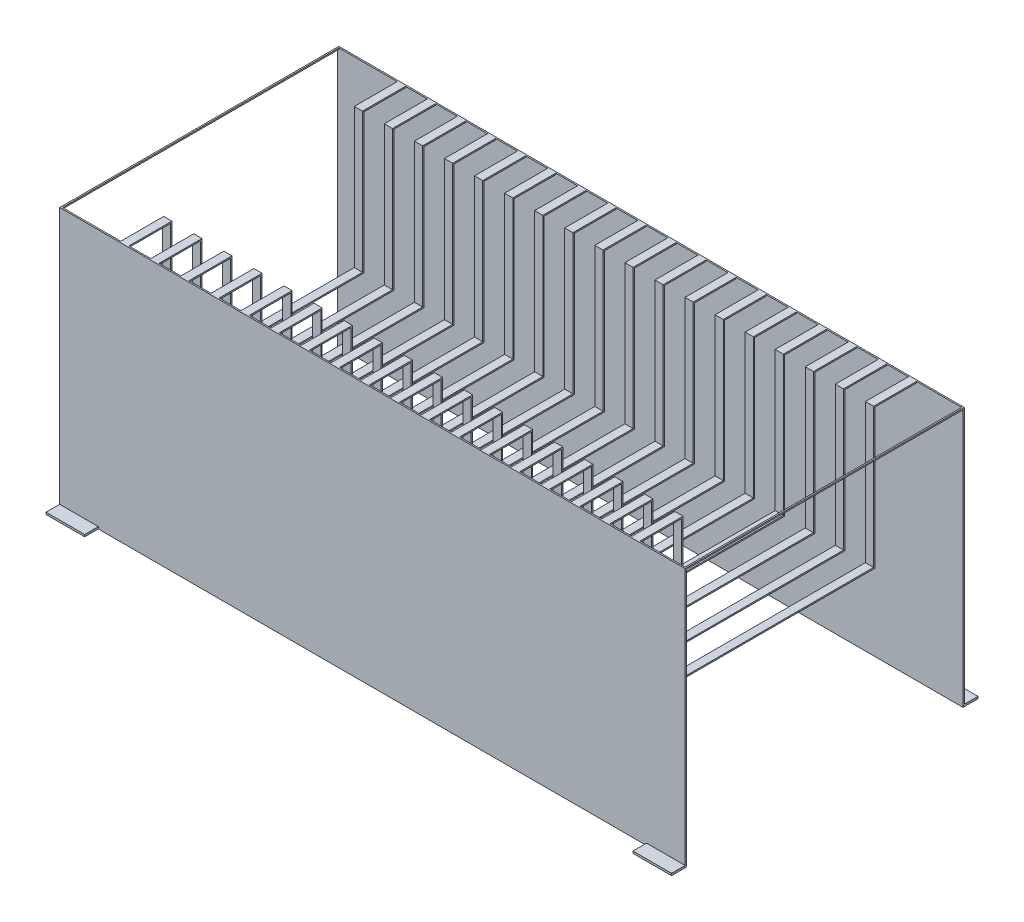
SolidWorks part; units mm, degrees
ref_plane "Alzado" through (0, 0, 0) normal (0, 0, 1) x (1, 0, 0)
ref_plane "Planta" through (0, 0, 0) normal (0, 1, 0) x (1, 0, 0)
ref_plane "Vista lateral" through (0, 0, 0) normal (1, 0, 0) x (0, 0, -1)
sketch "Croquis1" plane through (0, 0, 0) normal (0, 0, 1) x (1, 0, 0)
  line L0 (0, 0) -> (0, 1200)
  line L1 (0, 0) -> (2900, 0)
  line L2 (2900, 0) -> (2900, 1200)
  line L3 (2900, 1200) -> (0, 1200) construction
  line L4 (2906.35, -6.35) -> (2906.35, 1200)
  line L5 (-6.35, -6.35) -> (2906.35, -6.35)
  line L6 (-6.35, -6.35) -> (-6.35, 1200)
  line L7 (0, 1200) -> (-6.35, 1200)
  line L8 (2900, 1200) -> (2906.35, 1200)
  dimension "D1" = 1200
  dimension "D2" = 2900
  dimension "D3" = 6.35
extrude "Saliente-Extruir1" add sketch "Croquis1" along normal blind 1300
sketch "Croquis2" plane through (0, 0, 1300) normal (0, 0, 1) x (1, 0, 0)
  line L1 (-6.35, 1200) -> (2906.35, 1200)
  line L2 (-6.35, 1200) -> (-6.35, -6.35)
  line L3 (-6.35, -6.35) -> (2906.35, -6.35)
  line L4 (2906.35, 1200) -> (2906.35, -6.35)
extrude "Saliente-Extruir2" add sketch "Croquis2" against normal blind 6.35
sketch "Croquis3" plane through (0, 0, 0) normal (0, 0, -1) x (-1, 0, 0)
  line L1 (-2906.35, 1200) -> (6.35, 1200)
  line L2 (-2906.35, 1200) -> (-2906.35, -6.35)
  line L3 (-2906.35, -6.35) -> (6.35, -6.35)
  line L4 (6.35, 1200) -> (6.35, -6.35)
extrude "Saliente-Extruir3" add sketch "Croquis3" against normal blind 6.35
sketch "Croquis4" plane through (0, 1200, 0) normal (0, 1, 0) x (1, 0, 0)
  line L0 (2900, -1293.65) -> (0, -1293.65) construction
  line L1 (2690, -1293.65) -> (2651.9, -1293.65)
  line L2 (2690, -1293.65) -> (2690, -1093.65)
  line L3 (2690, -1093.65) -> (2651.9, -1093.65)
  line L4 (2651.9, -1293.65) -> (2651.9, -1093.65)
  line L5 (2900, -1293.65) -> (2900, -6.35) construction
  line L6 (2900, -650) -> (2322.7282, -650) construction
  line L7 (2900, -1293.65) -> (2900, -6.35) construction
  line L8 (2651.9, -6.35) -> (2651.9, -206.35)
  line L9 (2690, -206.35) -> (2651.9, -206.35)
  line L10 (2690, -6.35) -> (2690, -206.35)
  line L11 (2690, -6.35) -> (2651.9, -6.35)
  dimension "D1" = 210
  dimension "D2" = 38.1
  dimension "D3" = 200
extrude "Saliente-Extruir4" add sketch "Croquis4" against normal blind 6.35
pattern_linear "MatrizL1" count 18 spacing 140 along (-1, 0, 0) of "Saliente-Extruir4"
sketch "Croquis5" plane through (-6.35, 0, 0) normal (-1, 0, 0) x (0, 0, 1)
  line L1 (1293.65, 1193.65) -> (6.35, 1193.65)
  line L2 (1293.65, 1193.65) -> (1293.65, -13.1397)
  line L3 (1293.65, -13.1397) -> (6.35, -13.1397)
  line L4 (6.35, 1193.65) -> (6.35, -13.1397)
extrude "Cortar-Extruir1" cut sketch "Croquis5" against normal up to surface (2912.7 mm away) up to face at (2906.35, 596.825, 650)
sketch "Croquis6" plane through (0, 1193.65, 0) normal (0, -1, 0) x (1, 0, 0)
  line L0 (310, 206.35) -> (310, 6.35) construction
  line L1 (271.9, 206.35) -> (310, 206.35)
  line L2 (271.9, 206.35) -> (271.9, 200)
  line L3 (271.9, 200) -> (310, 200)
  line L4 (310, 206.35) -> (310, 200)
  dimension "D1" = 6.35
extrude "Saliente-Extruir5" add sketch "Croquis6" along normal blind 650
pattern_linear "MatrizL2" count 18 spacing 140 along (1, 0, 0) of "Saliente-Extruir5"
sketch "Croquis7" plane through (0, 1193.65, 0) normal (0, -1, 0) x (1, 0, 0)
  line L0 (2651.9, 1093.65) -> (2651.9, 1293.65) construction
  line L1 (2690, 1093.65) -> (2651.9, 1093.65)
  line L2 (2690, 1093.65) -> (2690, 1100)
  line L3 (2690, 1100) -> (2651.9, 1100)
  line L4 (2651.9, 1093.65) -> (2651.9, 1100)
  dimension "D1" = 6.35
extrude "Saliente-Extruir6" add sketch "Croquis7" along normal blind 650
pattern_linear "MatrizL3" count 18 spacing 140 along (-1, 0, 0) of "Saliente-Extruir6"
sketch "Croquis8" plane through (0, 0, 1093.65) normal (0, 0, -1) x (-1, 0, 0)
  line L0 (-2651.9, 543.65) -> (-2651.9, 1200) construction
  line L1 (-2690, 543.65) -> (-2651.9, 543.65)
  line L2 (-2690, 543.65) -> (-2690, 550)
  line L3 (-2690, 550) -> (-2651.9, 550)
  line L4 (-2651.9, 543.65) -> (-2651.9, 550)
  dimension "D1" = 6.35
extrude "Saliente-Extruir7" add sketch "Croquis8" along normal up to surface (887.3 mm away) up to face at (2670.95, 871.825, 206.35)
pattern_linear "MatrizL4" count 18 spacing 140 along (-1, 0, 0) of "Saliente-Extruir7"
sketch "Croquis9" plane through (0, -6.35, 0) normal (0, -1, 0) x (1, 0, 0)
  line L0 (2906.35, 650) -> (-120.3286, 650) construction
  line L1 (2906.35, 1300) -> (2726.35, 1300)
  line L2 (2906.35, 1300) -> (2906.35, 1363.5)
  line L3 (2906.35, 1363.5) -> (2726.35, 1363.5)
  line L4 (2726.35, 1300) -> (2726.35, 1363.5)
  line L5 (2906.35, 6.35) -> (2906.35, 1293.65) construction
  line L6 (2726.35, 0) -> (2726.35, -63.5)
  line L7 (2906.35, -63.5) -> (2726.35, -63.5)
  line L8 (2906.35, 0) -> (2906.35, -63.5)
  line L9 (2906.35, 0) -> (2726.35, 0)
  line L10 (1450, 1300) -> (1450, 748.066) construction
  line L11 (-6.35, 1300) -> (2906.35, 1300) construction
  line L12 (-6.35, 0) -> (173.65, 0)
  line L13 (-6.35, 0) -> (-6.35, -63.5)
  line L14 (-6.35, -63.5) -> (173.65, -63.5)
  line L15 (173.65, 0) -> (173.65, -63.5)
  line L16 (173.65, 1300) -> (173.65, 1363.5)
  line L17 (-6.35, 1363.5) -> (173.65, 1363.5)
  line L18 (-6.35, 1300) -> (-6.35, 1363.5)
  line L19 (-6.35, 1300) -> (173.65, 1300)
  line L20 (-6.35, 650) -> (3020.3286, 650) construction
  dimension "D1" = 63.5
  dimension "D2" = 180
extrude "Saliente-Extruir8" add sketch "Croquis9" against normal blind 9.525
